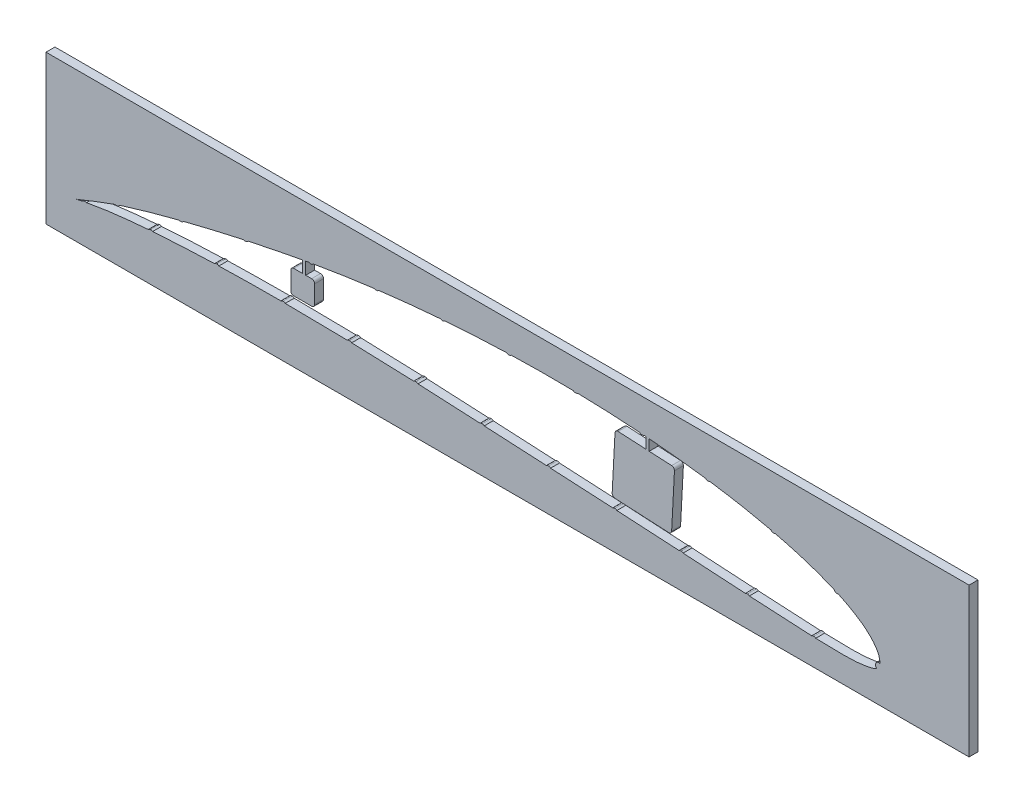
SolidWorks part; units mm, degrees
ref_plane "Front Plane" through (0, 0, 0) normal (0, 0, 1) x (1, 0, 0)
ref_plane "Top Plane" through (0, 0, 0) normal (0, 1, 0) x (1, 0, 0)
ref_plane "Right Plane" through (0, 0, 0) normal (1, 0, 0) x (0, 0, -1)
sketch "Sketch1" plane through (0, 0, 0) normal (0, 0, 1) x (1, 0, 0)
  line L0 (-190.854, 16.4273) -> (-196.854, 16.4273) construction
  line L1 (-280.0617, 37.7124) -> (29.9383, 37.7124)
  line L2 (-280.0617, 37.7124) -> (-280.0617, -12.2876)
  line L3 (-280.0617, -12.2876) -> (29.9383, -12.2876)
  line L4 (29.9383, 37.7124) -> (29.9383, -12.2876)
  line L5 (-197.854, 15.4273) -> (-197.854, 9.4273) construction
  line L6 (-196.854, 8.4273) -> (-190.854, 8.4273) construction
  line L7 (-189.854, 9.4273) -> (-189.854, 15.4273) construction
  line L8 (-69.9519, 22.5249) -> (-87.9272, 23.467) construction
  line L9 (-88.9782, 22.5207) -> (-89.9203, 4.5453) construction
  line L10 (-88.974, 3.4944) -> (-70.9986, 2.5523) construction
  line L11 (-69.9477, 3.4986) -> (-69.0056, 21.474) construction
  line L12 (-190.854, 16.4273) -> (-192.854, 16.4273)
  line L13 (-197.854, 15.4273) -> (-197.854, 9.4273)
  line L14 (-196.854, 8.4273) -> (-190.854, 8.4273)
  line L15 (-189.854, 9.4273) -> (-189.854, 15.4273)
  line L16 (-69.9519, 22.5249) -> (-77.4845, 22.9197)
  line L17 (-88.9782, 22.5207) -> (-89.9203, 4.5453)
  line L18 (-88.974, 3.4944) -> (-70.9986, 2.5523)
  line L19 (-69.9477, 3.4986) -> (-69.0056, 21.474)
  line L20 (-193.854, 16.4273) -> (-193.854, 20.3627)
  line L21 (-192.854, 16.4273) -> (-192.854, 20.5451)
  line L22 (-78.4845, 22.9721) -> (-78.4845, 26.6521)
  line L23 (-77.4845, 22.9197) -> (-77.4845, 26.5722)
  line L24 (-193.854, 16.4273) -> (-196.854, 16.4273)
  line L25 (-78.4845, 22.9721) -> (-87.9272, 23.467)
  arc A0 (-189.854, 15.4273) -> (-190.854, 16.4273) centre (-190.854, 15.4273) ccw construction
  arc A1 (-196.854, 16.4273) -> (-197.854, 15.4273) centre (-196.854, 15.4273) ccw construction
  arc A2 (-197.854, 9.4273) -> (-196.854, 8.4273) centre (-196.854, 9.4273) ccw construction
  arc A3 (-190.854, 8.4273) -> (-189.854, 9.4273) centre (-190.854, 9.4273) ccw construction
  arc A4 (-69.0056, 21.474) -> (-69.9519, 22.5249) centre (-70.0042, 21.5263) ccw construction
  arc A5 (-87.9272, 23.467) -> (-88.9782, 22.5207) centre (-87.9796, 22.4683) ccw construction
  arc A6 (-89.9203, 4.5453) -> (-88.974, 3.4944) centre (-88.9216, 4.493) ccw construction
  arc A7 (-70.9986, 2.5523) -> (-69.9477, 3.4986) centre (-70.9463, 3.551) ccw construction
  arc A8 (-189.854, 15.4273) -> (-190.854, 16.4273) centre (-190.854, 15.4273) ccw
  arc A9 (-196.854, 16.4273) -> (-197.854, 15.4273) centre (-196.854, 15.4273) ccw
  arc A10 (-197.854, 9.4273) -> (-196.854, 8.4273) centre (-196.854, 9.4273) ccw
  arc A11 (-190.854, 8.4273) -> (-189.854, 9.4273) centre (-190.854, 9.4273) ccw
  arc A12 (-69.0056, 21.474) -> (-69.9519, 22.5249) centre (-70.0042, 21.5263) ccw
  arc A13 (-87.9272, 23.467) -> (-88.9782, 22.5207) centre (-87.9796, 22.4683) ccw
  arc A14 (-89.9203, 4.5453) -> (-88.974, 3.4944) centre (-88.9216, 4.493) ccw
  arc A15 (-70.9986, 2.5523) -> (-69.9477, 3.4986) centre (-70.9463, 3.551) ccw
  spline S1 degree 3 poles (-193.854, 20.3627) (-195.7751, 20.0099) (-200.5374, 19.1048) (-208.0193, 17.5868) (-216.1682, 15.8177) (-223.9187, 14.036) (-231.2122, 12.2665) (-237.9937, 10.5351) (-244.2102, 8.86) (-249.8101, 7.2653) (-254.7614, 5.7542) (-259.0225, 4.2994) (-262.6484, 2.9195) (-265.4933, 1.7547) (-267.9068, 0.8001) (-268.9329, 0.3525) (-270.2805, -0.0806) (-268.8608, 0.2788) (-267.6685, 0.4898) (-264.7489, 1.0836) (-261.0889, 1.668) (-256.239, 2.3104) (-250.4593, 2.9183) (-243.7431, 3.4847) (-236.1813, 3.9747) (-227.8386, 4.3681) (-218.7963, 4.6499) (-209.1363, 4.8086) (-198.945, 4.8392) (-188.3105, 4.7407) (-177.322, 4.5164) (-166.073, 4.1742) (-154.6659, 3.7041) (-143.2011, 3.1378) (-131.7579, 2.5421) (-120.3938, 1.9439) (-109.1579, 1.3676) (-98.1107, 0.7936) (-87.3251, 0.2099) (-76.8781, -0.3783) (-66.8468, -0.9614) (-57.305, -1.5317) (-48.3225, -2.0715) (-39.9657, -2.5702) (-32.2954, -3.0045) (-25.3684, -3.3609) (-19.2374, -3.6152) (-13.9401, -3.7323) (-9.5038, -3.671) (-5.9009, -3.4146) (-3.1916, -2.8616) (-1.1702, -2.329) (0.0142, -1.0346) (0.0282, 0.6149) (-0.3711, 2.3888) (-1.479, 4.2931) (-3.1624, 6.2613) (-5.4722, 8.2745) (-8.4191, 10.259) (-11.9757, 12.2431) (-16.1613, 14.1676) (-20.9568, 16.0158) (-26.3378, 17.7935) (-32.2855, 19.4683) (-38.7673, 21.0309) (-45.7522, 22.4644) (-53.2043, 23.7511) (-61.0839, 24.8872) (-69.223, 25.8396) (-74.736, 26.3488) (-77.4845, 26.5722) knots 0.857235 0.857235 0.857235 0.857235 0.867829 0.883529 0.898645 0.913061 0.926666 0.939355 0.951026 0.961586 0.970943 0.979085 0.98606 0.991821 0.996214 0.999021 1 1.000989 1.003951 1.008893 1.015821 1.024635 1.035204 1.047421 1.061167 1.076314 1.09272 1.110239 1.128718 1.148001 1.167926 1.188336 1.209047 1.229854 1.250601 1.271203 1.291583 1.311629 1.331208 1.350174 1.368387 1.385714 1.402025 1.4172 1.431125 1.443698 1.454823 1.464413 1.472429 1.478905 1.483926 1.487499 1.490013 1.49277 1.496008 1.499868 1.504544 1.51003 1.516427 1.523784 1.532099 1.541394 1.551649 1.562829 1.574902 1.587809 1.6015 1.615917 1.630988 1.645946 1.645946 1.645946 1.645946
  spline S2 degree 3 poles (-78.4845, 26.6521) (-81.2511, 26.8696) (-87.0734, 27.263) (-96.0259, 27.668) (-105.3849, 27.8869) (-114.898, 27.9027) (-124.5158, 27.7065) (-134.1907, 27.3179) (-143.8738, 26.7206) (-153.5144, 25.926) (-163.0672, 24.9496) (-172.4857, 23.7789) (-181.7291, 22.4466) (-188.4962, 21.3268) (-192.1776, 20.6678) (-192.854, 20.5451) knots 1.64776 1.64776 1.64776 1.64776 1.662813 1.679411 1.696367 1.71359 1.73101 1.748545 1.766109 1.783631 1.801013 1.818193 1.83511 1.851668 1.855397 1.855397 1.855397 1.855397
  dimension "D1" = 50
  dimension "D2" = 310
  dimension "D3" = 1
  dimension "D4" = 1
extrude "Boss-Extrude1" add sketch "Sketch1" along normal blind 3 contours L16 L23 S1 L20 L24 A9 L13 A10 L14 A11 L15 A8 L12 L21 S2 L22 L25 A13 L17 A14 L18 A15 L19 A12 | L2 L1 L4 L3
sketch "Sketch3" plane through (0, 0, 3) normal (0, 0, 1) x (1, 0, 0)
  spline S1 degree 3 poles (-268.9329, 0.3525) (-270.2805, -0.0806) (-268.8608, 0.2788) (-267.6685, 0.4898) (-264.7489, 1.0836) (-261.0889, 1.668) (-256.239, 2.3104) (-250.4593, 2.9183) (-243.7431, 3.4847) (-236.1813, 3.9747) (-227.8386, 4.3681) (-218.7963, 4.6499) (-209.1363, 4.8086) (-198.945, 4.8392) (-188.3105, 4.7407) (-177.322, 4.5164) (-166.073, 4.1742) (-154.6659, 3.7041) (-143.2011, 3.1378) (-131.7579, 2.5421) (-120.3938, 1.9439) (-109.1579, 1.3676) (-98.1107, 0.7936) (-87.3251, 0.2099) (-76.8781, -0.3783) (-66.8468, -0.9614) (-57.305, -1.5317) (-48.3225, -2.0715) (-39.9657, -2.5702) (-32.2954, -3.0045) (-25.3684, -3.3609) (-19.2374, -3.6152) (-13.9401, -3.7323) (-9.5038, -3.671) (-5.9009, -3.4146) (-3.1916, -2.8616) (-1.1702, -2.329) (0.0142, -1.0346) (0.0282, 0.6149) (-0.3711, 2.3888) (-1.479, 4.2931) (-3.1624, 6.2613) (-5.4722, 8.2745) (-8.4191, 10.259) (-11.9757, 12.2431) (-16.1613, 14.1676) (-20.9568, 16.0158) (-26.3378, 17.7935) (-32.2855, 19.4683) (-38.7673, 21.0309) (-45.7522, 22.4644) (-53.2043, 23.7511) (-61.0839, 24.8872) (-69.3513, 25.8546) (-77.9613, 26.6449) (-86.8684, 27.2538) (-96.0259, 27.668) (-105.3849, 27.8869) (-114.898, 27.9027) (-124.5158, 27.7065) (-134.1907, 27.3179) (-143.8738, 26.7206) (-153.5144, 25.926) (-163.0672, 24.9496) (-172.4857, 23.7789) (-181.7291, 22.4466) (-190.7576, 20.9527) (-199.5316, 19.3088) (-208.0193, 17.5868) (-216.1682, 15.8177) (-223.9187, 14.036) (-231.2122, 12.2665) (-237.9937, 10.5351) (-244.2102, 8.86) (-249.8101, 7.2653) (-254.7614, 5.7542) (-259.0225, 4.2994) (-262.6484, 2.9195) (-265.4933, 1.7547) (-267.9068, 0.8001) (-268.9329, 0.3525) (-270.2805, -0.0806) (-268.8608, 0.2788) knots -0.008179 -0.003786 -0.000979 0 0.000989 0.003951 0.008893 0.015821 0.024635 0.035204 0.047421 0.061167 0.076314 0.09272 0.110239 0.128718 0.148001 0.167926 0.188336 0.209047 0.229854 0.250601 0.271203 0.291583 0.311629 0.331208 0.350174 0.368387 0.385714 0.402025 0.4172 0.431125 0.443698 0.454823 0.464413 0.472429 0.478905 0.483926 0.487499 0.490013 0.49277 0.496008 0.499868 0.504544 0.51003 0.516427 0.523784 0.532099 0.541394 0.551649 0.562829 0.574902 0.587809 0.6015 0.615917 0.630988 0.646647 0.662813 0.679411 0.696367 0.71359 0.73101 0.748545 0.766109 0.783631 0.801013 0.818193 0.83511 0.851668 0.867829 0.883529 0.898645 0.913061 0.926666 0.939355 0.951026 0.961586 0.970943 0.979085 0.98606 0.991821 0.996214 0.999021 1 1.000989 1.003951 1.008893 only from (-270, 0) to (-270, 0) construction
  spline S2 degree 3 poles (-268.9329, 0.3525) (-270.2805, -0.0806) (-268.8608, 0.2788) (-267.6685, 0.4898) (-264.7489, 1.0836) (-261.0889, 1.668) (-256.239, 2.3104) (-250.4593, 2.9183) (-243.7431, 3.4847) (-236.1813, 3.9747) (-227.8386, 4.3681) (-218.7963, 4.6499) (-209.1363, 4.8086) (-198.945, 4.8392) (-188.3105, 4.7407) (-177.322, 4.5164) (-166.073, 4.1742) (-154.6659, 3.7041) (-143.2011, 3.1378) (-131.7579, 2.5421) (-120.3938, 1.9439) (-109.1579, 1.3676) (-98.1107, 0.7936) (-87.3251, 0.2099) (-76.8781, -0.3783) (-66.8468, -0.9614) (-57.305, -1.5317) (-48.3225, -2.0715) (-39.9657, -2.5702) (-32.2954, -3.0045) (-25.3684, -3.3609) (-19.2374, -3.6152) (-13.9401, -3.7323) (-9.5038, -3.671) (-5.9009, -3.4146) (-3.1916, -2.8616) (-1.1702, -2.329) (0.0142, -1.0346) (0.0282, 0.6149) (-0.3711, 2.3888) (-1.479, 4.2931) (-3.1624, 6.2613) (-5.4722, 8.2745) (-8.4191, 10.259) (-11.9757, 12.2431) (-16.1613, 14.1676) (-20.9568, 16.0158) (-26.3378, 17.7935) (-32.2855, 19.4683) (-38.7673, 21.0309) (-45.7522, 22.4644) (-53.2043, 23.7511) (-61.0839, 24.8872) (-69.3513, 25.8546) (-77.9613, 26.6449) (-86.8684, 27.2538) (-96.0259, 27.668) (-105.3849, 27.8869) (-114.898, 27.9027) (-124.5158, 27.7065) (-134.1907, 27.3179) (-143.8738, 26.7206) (-153.5144, 25.926) (-163.0672, 24.9496) (-172.4857, 23.7789) (-181.7291, 22.4466) (-190.7576, 20.9527) (-199.5316, 19.3088) (-208.0193, 17.5868) (-216.1682, 15.8177) (-223.9187, 14.036) (-231.2122, 12.2665) (-237.9937, 10.5351) (-244.2102, 8.86) (-249.8101, 7.2653) (-254.7614, 5.7542) (-259.0225, 4.2994) (-262.6484, 2.9195) (-265.4933, 1.7547) (-267.9068, 0.8001) (-268.9329, 0.3525) (-270.2805, -0.0806) (-268.8608, 0.2788) knots -0.008179 -0.003786 -0.000979 0 0.000989 0.003951 0.008893 0.015821 0.024635 0.035204 0.047421 0.061167 0.076314 0.09272 0.110239 0.128718 0.148001 0.167926 0.188336 0.209047 0.229854 0.250601 0.271203 0.291583 0.311629 0.331208 0.350174 0.368387 0.385714 0.402025 0.4172 0.431125 0.443698 0.454823 0.464413 0.472429 0.478905 0.483926 0.487499 0.490013 0.49277 0.496008 0.499868 0.504544 0.51003 0.516427 0.523784 0.532099 0.541394 0.551649 0.562829 0.574902 0.587809 0.6015 0.615917 0.630988 0.646647 0.662813 0.679411 0.696367 0.71359 0.73101 0.748545 0.766109 0.783631 0.801013 0.818193 0.83511 0.851668 0.867829 0.883529 0.898645 0.913061 0.926666 0.939355 0.951026 0.961586 0.970943 0.979085 0.98606 0.991821 0.996214 0.999021 1 1.000989 1.003951 1.008893 only from (-270, 0) to (-270, 0) construction
  text T0 "........................." font "Century Gothic" height 14
  point P3 (0, 0)
  point P4 (0, 0)
  point P5 (-264.7876, 1.0521)
extrude "Boss-Extrude2" add sketch "Sketch3" against normal blind 3
